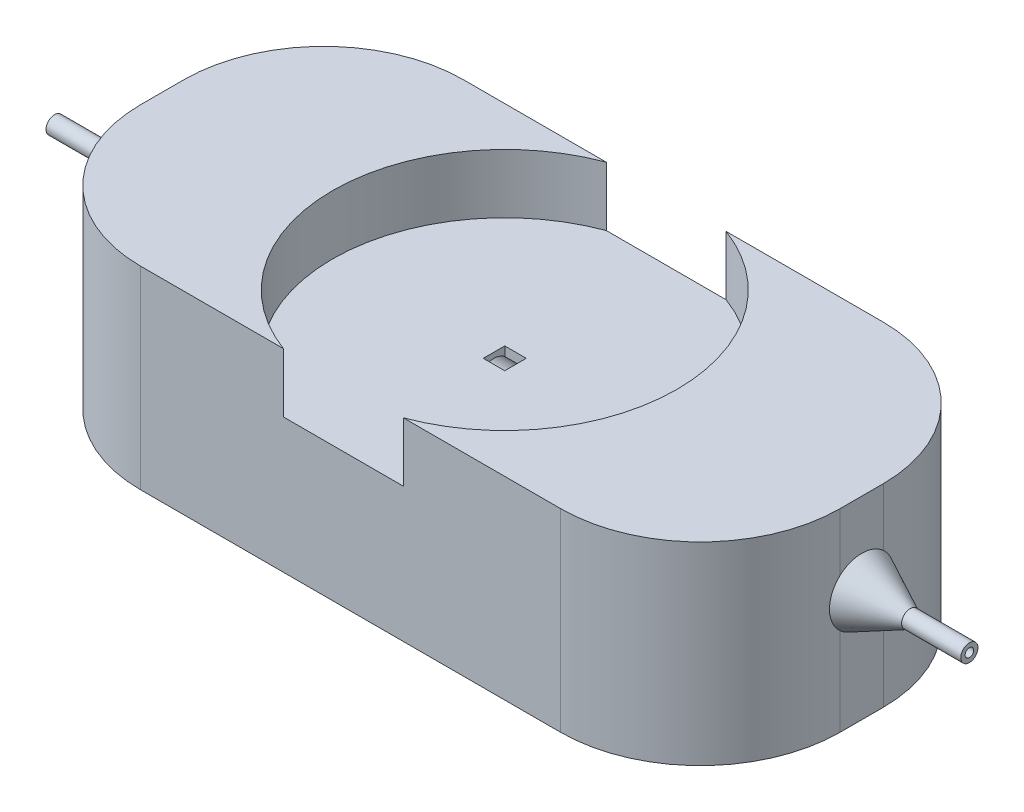
SolidWorks part; units mm, degrees
ref_plane "Front Plane" through (0, 0, 0) normal (0, 0, 1) x (1, 0, 0)
ref_plane "Top Plane" through (0, 0, 0) normal (0, 1, 0) x (1, 0, 0)
ref_plane "Right Plane" through (0, 0, 0) normal (1, 0, 0) x (0, 0, -1)
sketch "Sketch1" plane through (0, 0, 0) normal (0, 1, 0) x (1, 0, 0)
  line L1 (-25, -15) -> (40, -15)
  line L2 (-25, -15) -> (-25, 15)
  line L3 (-25, 15) -> (40, 15)
  line L4 (40, -15) -> (40, 15)
  line L5 (-25, -15) -> (40, 15) construction
  line L6 (-25, 15) -> (40, -15) construction
  point P0 (0, 0)
  dimension "D1" = 30
  dimension "D2" = 65
extrude "Boss-Extrude1" add sketch "Sketch1" along normal blind 58
sketch "Sketch3" plane through (-25, 0, 0) normal (-1, 0, 0) x (0, 0, 1)
  line L0 (-15, 58) -> (15, 58) construction
  circle A0 centre (0, 50.4) radius 1.6
  dimension "D1" = 3.2
  dimension "D2" = 7.6
fillet "Fillet1" radius 13 4 edges at (40, 29, -15) (-25, 29, -15) (40, 29, 15) (-25, 29, 15)
ref_plane "Plane2" through (0, -10, 0) normal (0, -1, 0) x (-1, 0, 0)
sketch "Sketch15" plane through (0, -10, 0) normal (0, -1, 0) x (-1, 0, 0)
  line L1 (-41.9055, 15.8797) -> (41.7906, 15.8797)
  line L2 (-41.9055, 15.8797) -> (-41.9055, -15.8187)
  line L3 (-41.9055, -15.8187) -> (41.7906, -15.8187)
  line L4 (41.7906, 15.8797) -> (41.7906, -15.8187)
extrude "Cut-Extrude7" cut sketch "Sketch15" against normal blind 50
ref_plane "Plane3" through (0, 40, 0) normal (0, -1, 0) x (-1, 0, 0)
ref_plane "Plane4" through (0, 58, 0) normal (0, 1, 0) x (1, 0, 0)
sketch "Sketch18" plane through (0, 58, 0) normal (0, 1, 0) x (1, 0, 0)
  circle A0 centre (6.8285, 0) radius 16
  dimension "D1" = 32
extrude "Cut-Extrude10" cut sketch "Sketch18" against normal blind 5.5
extrude "Cut-Extrude12" cut sketch "Sketch3" against normal up to next
ref_plane "Plane5" through (0, 52.5, 0) normal (0, 1, 0) x (1, 0, 0)
sketch "Sketch21" plane through (0, 52.5, 0) normal (0, 1, 0) x (1, 0, 0)
  line L1 (5.8285, -1) -> (7.8285, -1)
  line L2 (5.8285, -1) -> (5.8285, 1)
  line L3 (5.8285, 1) -> (7.8285, 1)
  line L4 (7.8285, -1) -> (7.8285, 1)
  line L5 (5.8285, -1) -> (7.8285, 1) construction
  line L6 (5.8285, 1) -> (7.8285, -1) construction
  point P0 (6.8285, 0)
  dimension "D1" = 2
  dimension "D2" = 2
extrude "Cut-Extrude13" cut sketch "Sketch21" against normal blind 8
ref_plane "Plane7" through (-25, 0, 0) normal (-1, 0, 0) x (0, 0, 1)
sketch "Sketch24" plane through (0, 0, 0) normal (0, 0, 1) x (1, 0, 0)
  line L1 (-25, 52) -> (-25, 48.8) construction
  line L5 (-25, 50.4) -> (-31.2466, 50.4) construction
  line L7 (-25, 50.4) -> (46.09, 50.4) construction
  line L8 (-25, 50.8) -> (-35, 50.8)
  line L9 (-29.5, 51.2) -> (-35, 51.2)
  line L10 (-35, 51.2) -> (-35, 50.8)
  line L11 (-25, 40) -> (-25, 58) construction
  line L12 (-29.5, 51.2) -> (-25, 53.4)
  line L13 (-25, 50.8) -> (-25, 53.4)
  dimension "D1" = 0.4
  dimension "D2" = 6
  dimension "D3" = 0.8
  dimension "D4" = 10
  dimension "D5" = 4.5
revolve "Revolve1" add sketch "Sketch24" angle 360 about L5
sketch "Sketch25" plane through (0, 0, 0) normal (0, 0, 1) x (1, 0, 0)
  line L1 (50.4822, 50.3986) -> (44.2356, 50.3986) construction
  line L13 (40, 50.7986) -> (40, 53.3986)
  line L14 (40, 58) -> (40, 40) construction
  line L15 (40, 53.3986) -> (44.5, 51.1986)
  line L16 (44.5, 51.1986) -> (50, 51.1986)
  line L17 (50, 51.1986) -> (50, 50.7986)
  line L18 (50, 50.7986) -> (40, 50.7986)
  dimension "D1" = 0.4
  dimension "D2" = 0.8
  dimension "D3" = 10
  dimension "D4" = 6
  dimension "D5" = 4.5
revolve "Revolve2" add sketch "Sketch25" angle 360 about L1
